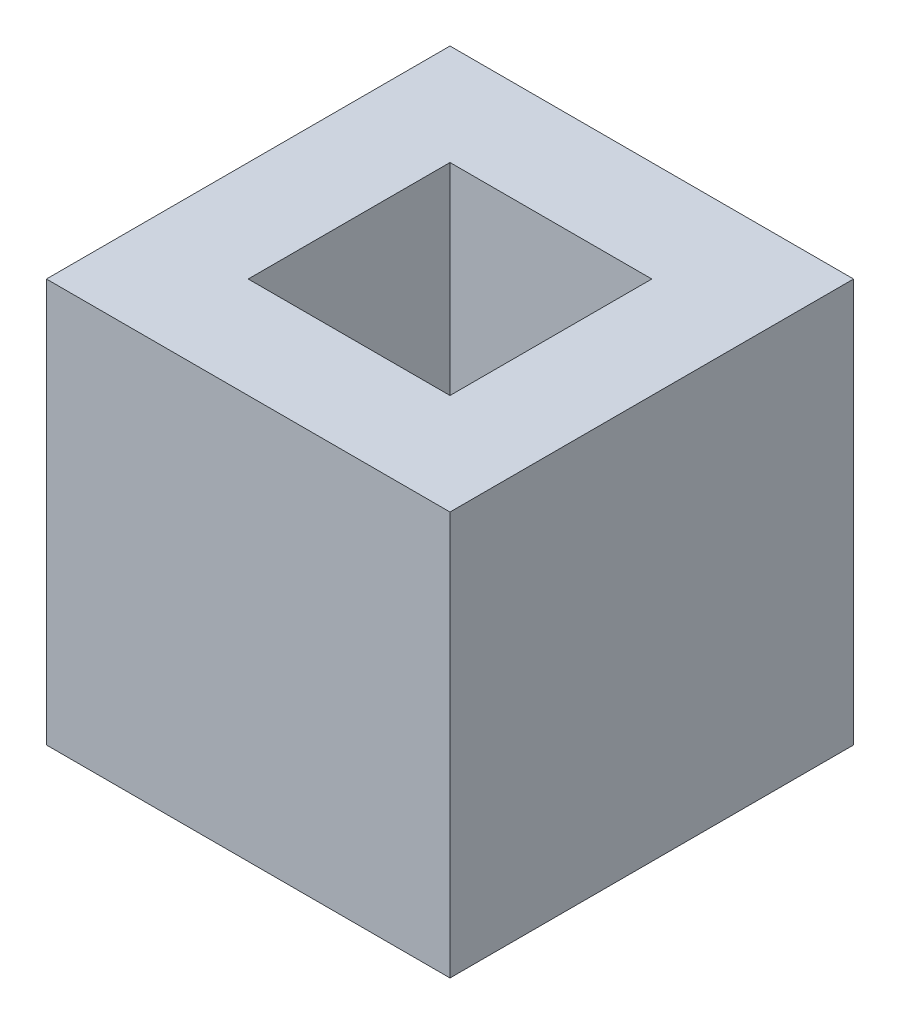
SolidWorks part; units mm, degrees
ref_plane "Front Plane" through (0, 0, 0) normal (0, 0, 1) x (1, 0, 0)
ref_plane "Top Plane" through (0, 0, 0) normal (0, 1, 0) x (1, 0, 0)
ref_plane "Right Plane" through (0, 0, 0) normal (1, 0, 0) x (0, 0, -1)
sketch "Sketch1" plane through (0, 0, 0) normal (0, 1, 0) x (1, 0, 0)
  line L1 (-2.5, 2.5) -> (2.5, 2.5)
  line L2 (-2.5, 2.5) -> (-2.5, -2.5)
  line L3 (-2.5, -2.5) -> (2.5, -2.5)
  line L4 (2.5, 2.5) -> (2.5, -2.5)
  line L5 (-2.5, 2.5) -> (2.5, -2.5) construction
  line L6 (-2.5, -2.5) -> (2.5, 2.5) construction
  line L7 (-5, 5) -> (5, 5)
  line L8 (-5, 5) -> (-5, -5)
  line L9 (-5, -5) -> (5, -5)
  line L10 (5, 5) -> (5, -5)
  line L11 (-5, 5) -> (5, -5) construction
  line L12 (-5, -5) -> (5, 5) construction
  point P0 (0, 0)
  point P6 (0, 0)
  dimension "D1" = 10
  dimension "D2" = 5
extrude "Boss-Extrude1" add sketch "Sketch1" along normal blind 10
